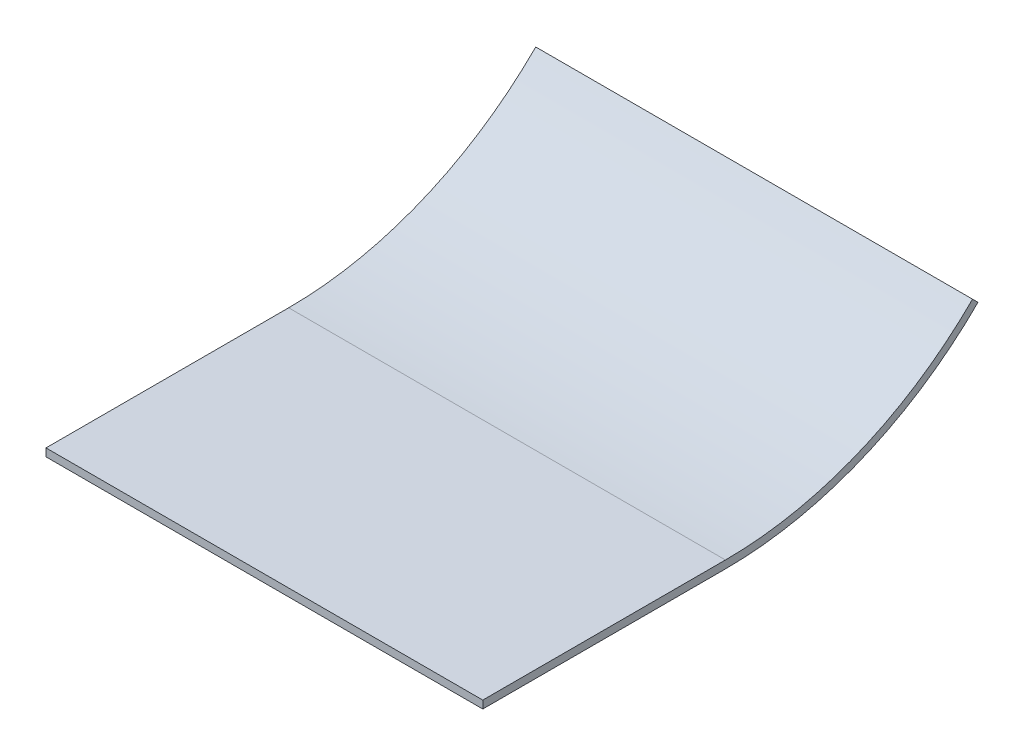
SolidWorks part; units mm, degrees
ref_plane "前视基准面" through (0, 0, 0) normal (0, 0, 1) x (1, 0, 0)
ref_plane "上视基准面" through (0, 0, 0) normal (0, 1, 0) x (1, 0, 0)
ref_plane "右视基准面" through (0, 0, 0) normal (1, 0, 0) x (0, 0, -1)
sketch "草图1" plane through (0, 0, 0) normal (1, 0, 0) x (0, 0, -1)
  line L0 (0, 0) -> (25, 0)
  line L1 (25, 36) -> (25, 0) construction
  line L2 (50.4558, 10.5442) -> (25, 36) construction
  arc A0 (25, 0) -> (50.4558, 10.5442) centre (25, 36) ccw
  point P5 (75.4093, 10.5442)
  dimension "D1" = 36
  dimension "D2" = 45
  dimension "D3" = 25
extrude "拉伸-薄壁1" add sketch "草图1" along normal blind 45 thin
